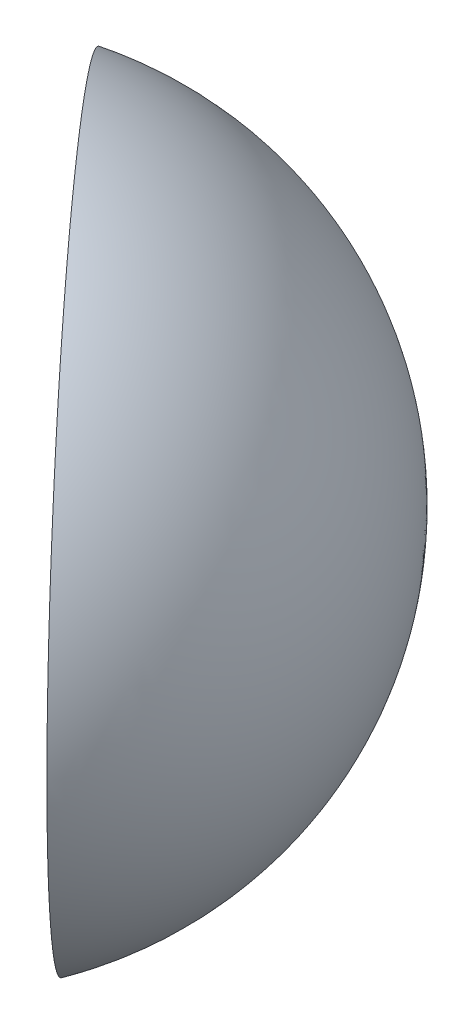
SolidWorks part; units mm, degrees
ref_plane "Front Plane" through (0, 0, 0) normal (0, 0, 1) x (1, 0, 0)
ref_plane "Top Plane" through (0, 0, 0) normal (0, 1, 0) x (1, 0, 0)
ref_plane "Right Plane" through (0, 0, 0) normal (1, 0, 0) x (0, 0, -1)
sketch "Sketch2" plane through (0, 0, 0) normal (0, 1, 0) x (1, 0, 0)
  line L0 (-13.4034, 21.6759) -> (-11.5183, 19.5067)
  arc A0 (-13.4034, 21.6759) -> (-11.5183, 19.5067) centre (-12.7857, 20.309) cw
sketch "Sketch4" plane through (0, 0, 0) normal (0, 1, 0) x (1, 0, 0)
  line L0 (-12.4608, 20.5913) -> (-11.6535, 21.2929) construction
  line L1 (-13.4034, 21.6759) -> (-11.5183, 19.5067) construction
  line L2 (-12.4608, 20.5913) -> (-11.6535, 21.2929)
  line L3 (-13.4034, 21.6759) -> (-12.4608, 20.5913)
  arc A0 (-11.5183, 19.5067) -> (-13.4034, 21.6759) centre (-12.7857, 20.309) ccw construction
  arc A1 (-13.4034, 21.6759) -> (-11.6535, 21.2929) centre (-12.7842, 20.3157) cw
revolve "Revolve10" add sketch "Sketch4" angle 360 about L2
